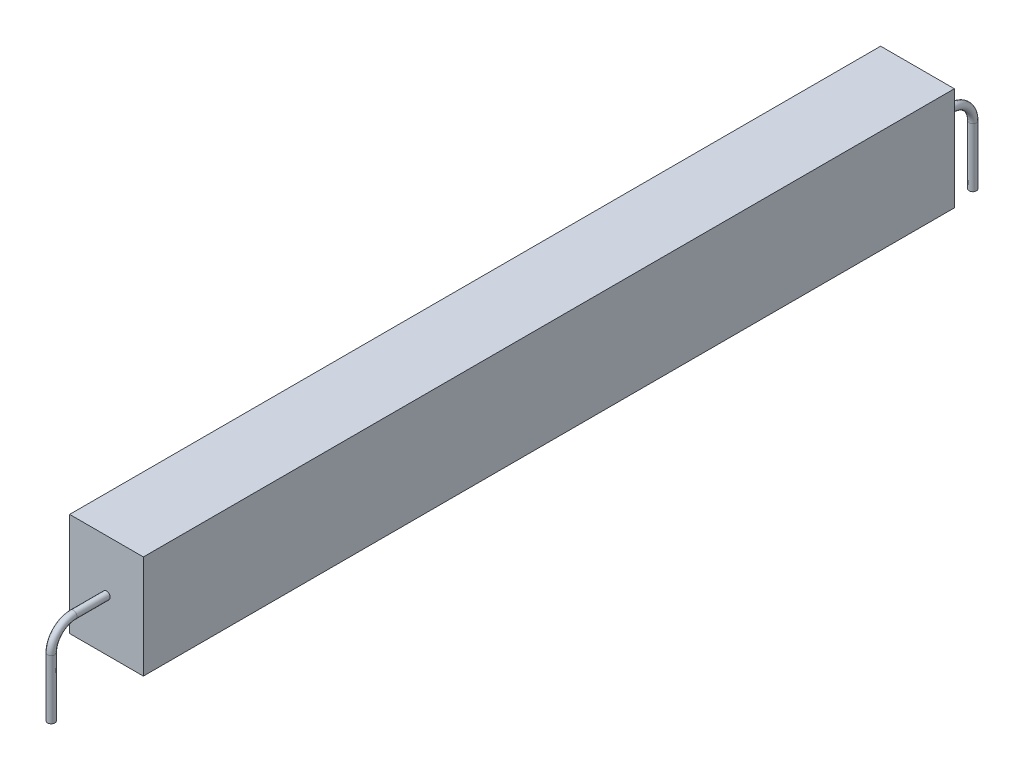
SolidWorks part; units mm, degrees
ref_plane "Спереди" through (0, 0, 0) normal (0, 0, 1) x (1, 0, 0)
ref_plane "Сверху" through (0, 0, 0) normal (0, 1, 0) x (1, 0, 0)
ref_plane "Справа" through (0, 0, 0) normal (1, 0, 0) x (0, 0, -1)
sketch "Эскиз1" plane through (0, 0, 0) normal (0, 0, 1) x (1, 0, 0)
  line L1 (-5, 14) -> (5, 14)
  line L2 (-5, 14) -> (-5, 0)
  line L3 (-5, 0) -> (5, 0)
  line L4 (5, 14) -> (5, 0)
  line L5 (-5, 14) -> (5, 0) construction
  line L6 (-5, 0) -> (5, 14) construction
  point P0 (0, 0)
extrude "Бобышка-Вытянуть1" add sketch "Эскиз1" against normal mid plane 110
sketch "Эскиз3" plane through (0, 0, 55) normal (0, 0, 1) x (1, 0, 0)
  circle A0 centre (0, 7) radius 0.5
sketch "Эскиз4" plane through (0, 0, 0) normal (1, 0, 0) x (0, 0, -1)
  line L0 (-62.5, -4) -> (-62.5, 4)
  line L1 (-59.5, 7) -> (-55, 7)
  line L2 (-55, 7.5) -> (-55, 6.5) construction
  arc A0 (-62.5, 4) -> (-59.5, 7) centre (-59.5, 4) cw
  dimension "D1" = 3
sweep "По траектории1" add profiles "Эскиз3" path "Эскиз4"
mirror "Зеркальное отражение1" about plane through (0, 0, 0) normal (0, 0, 1) of "По траектории1"
